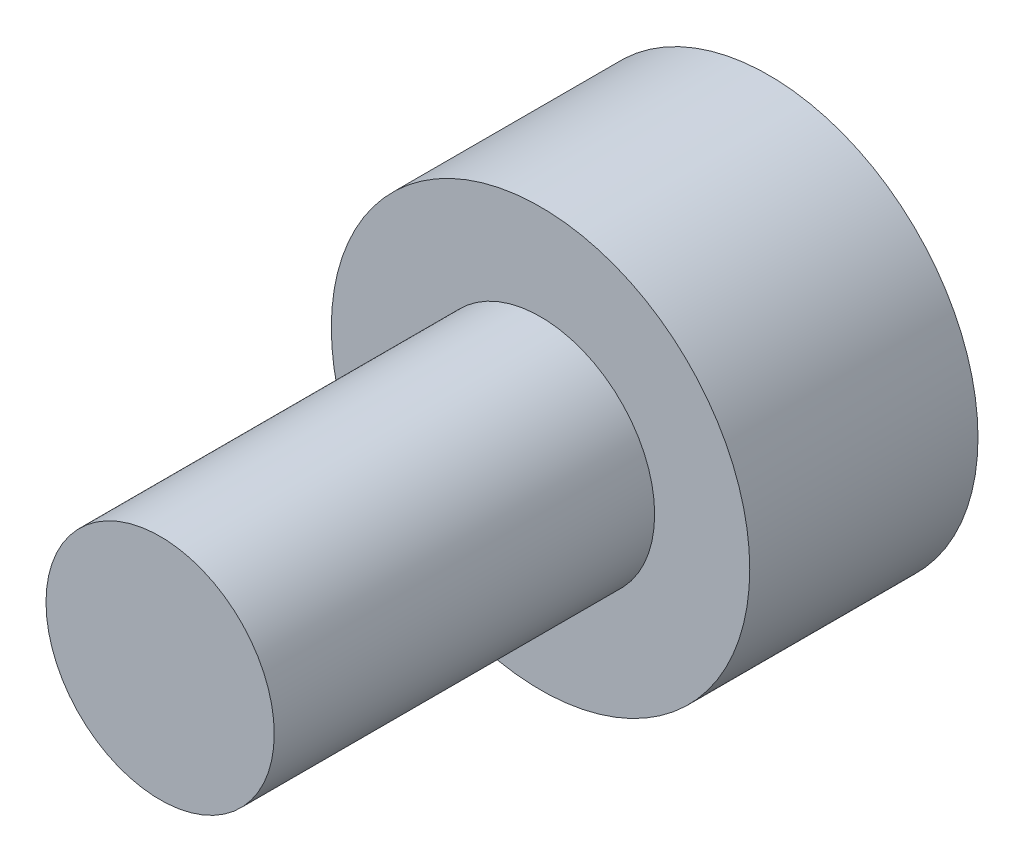
SolidWorks part; units mm, degrees
other "DetailItem1"
material "Chrome Stainless Steel"
ref_plane "Front Plane" through (0, 0, 0) normal (0, 0, 1) x (1, 0, 0)
ref_plane "Top Plane" through (0, 0, 0) normal (0, 1, 0) x (1, 0, 0)
ref_plane "Right Plane" through (0, 0, 0) normal (1, 0, 0) x (0, 0, -1)
sketch "Sketch1" plane through (0, 0, 0) normal (0, 0, 1) x (1, 0, 0)
  circle A0 centre (0, 0) radius 1.5
  dimension "OD" = 3
extrude "Extrude1" add sketch "Sketch1" against normal blind 5
sketch "Sketch6" plane through (0, 0, -5) normal (0, 0, -1) x (-1, 0, 0)
  circle A0 centre (0, 0) radius 2.75
  dimension "head dia" = 5.5
extrude "Extrude2" add sketch "Sketch6" along normal blind 3
sketch "Sketch7" plane through (0, 0, -8) normal (0, 0, -1) x (-1, 0, 0)
  line L1 (0, 1.4434) -> (-1.25, 0.7217)
  line L2 (-1.25, 0.7217) -> (-1.25, -0.7217)
  line L3 (-1.25, -0.7217) -> (0, -1.4434)
  line L4 (0, -1.4434) -> (1.25, -0.7217)
  line L5 (1.25, -0.7217) -> (1.25, 0.7217)
  line L6 (1.25, 0.7217) -> (0, 1.4434)
  circle A0 centre (0, 0) radius 1.25 construction
  dimension "hex dia" = 2.5
extrude "Cut-Extrude1" cut sketch "Sketch7" against normal blind 1.875
equation "\"D1@Cut-Extrude1\" = \"hex dia@Sketch7\"*.75"
